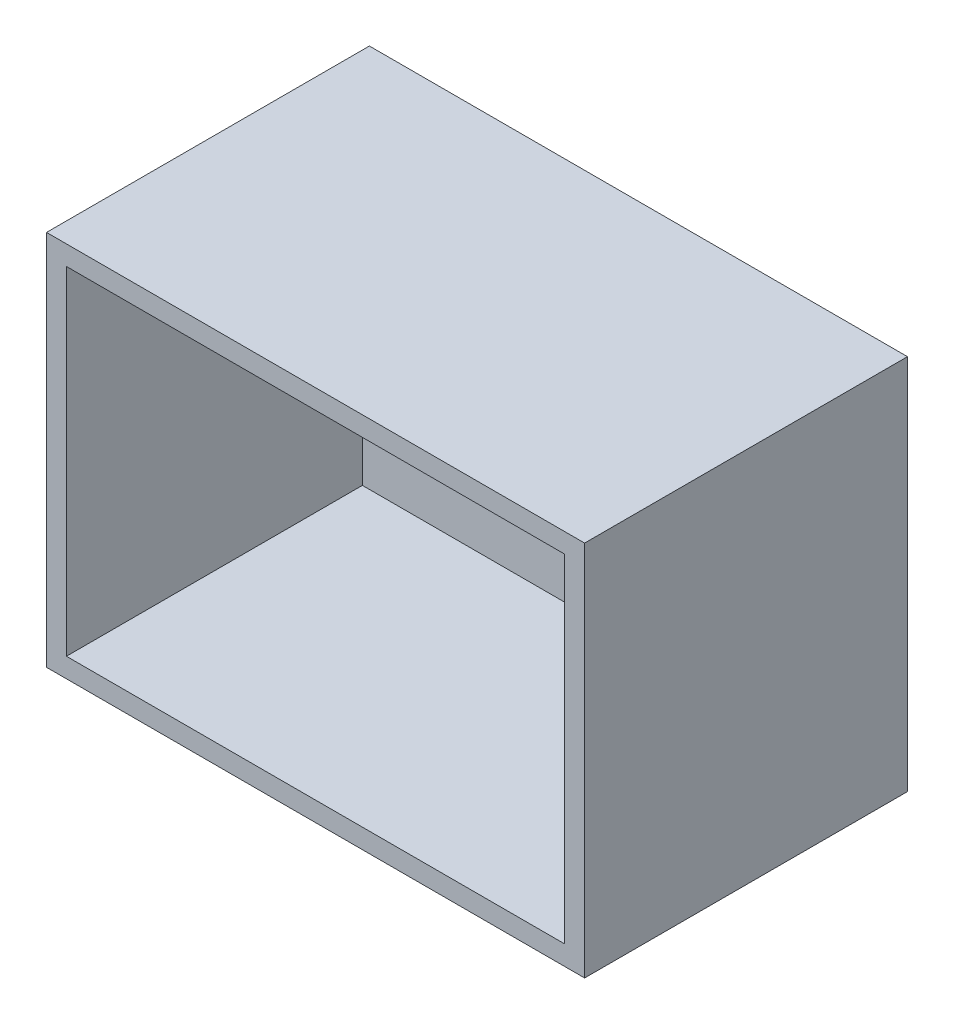
SolidWorks part; units mm, degrees
material "Glass"
ref_plane "Front Plane" through (0, 0, 0) normal (0, 0, 1) x (1, 0, 0)
ref_plane "Top Plane" through (0, 0, 0) normal (0, 1, 0) x (1, 0, 0)
ref_plane "Right Plane" through (0, 0, 0) normal (1, 0, 0) x (0, 0, -1)
sketch "Sketch1" plane through (0, 0, 0) normal (0, 0, 1) x (1, 0, 0)
  line L1 (0, 0) -> (100, 0)
  line L2 (0, 0) -> (0, 70)
  line L3 (0, 70) -> (100, 70)
  line L4 (100, 0) -> (100, 70)
  dimension "D1" = 100
  dimension "D2" = 70
extrude "Boss-Extrude1" add sketch "Sketch1" along normal blind 60
sketch "Sketch2" plane through (0, 0, 60) normal (0, 0, 1) x (1, 0, 0)
  line L1 (3.7006, 3.6328) -> (96.2994, 3.6328)
  line L2 (3.7006, 3.6328) -> (3.7006, 66.3672)
  line L3 (3.7006, 66.3672) -> (96.2994, 66.3672)
  line L4 (96.2994, 3.6328) -> (96.2994, 66.3672)
  line L5 (3.7006, 3.6328) -> (96.2994, 66.3672) construction
  line L6 (3.7006, 66.3672) -> (96.2994, 3.6328) construction
  point P0 (50, 35)
extrude "Cut-Extrude1" cut sketch "Sketch2" against normal blind 55
